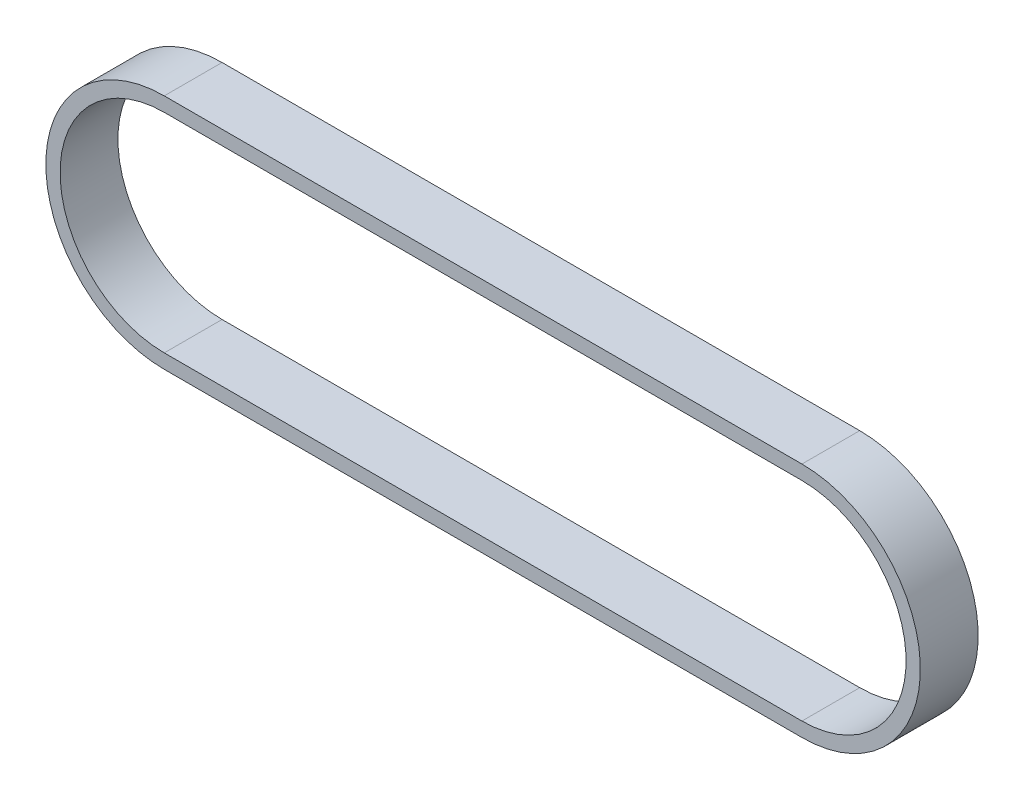
SolidWorks part; units mm, degrees
ref_plane "Plano frontal" through (0, 0, 0) normal (0, 0, 1) x (1, 0, 0)
ref_plane "Plano superior" through (0, 0, 0) normal (0, 1, 0) x (1, 0, 0)
ref_plane "Plano direito" through (0, 0, 0) normal (1, 0, 0) x (0, 0, -1)
sketch "Esboço1" plane through (0, 0, 0) normal (0, 0, 1) x (1, 0, 0)
  line L0 (0, 0) -> (105, 0) construction
  line L1 (0, 19.5) -> (105, 19.5)
  line L2 (0, -19.5) -> (105, -19.5)
  line L3 (0, 17.15) -> (105, 17.15)
  line L4 (0, -17.15) -> (105, -17.15)
  arc A0 (0, 19.5) -> (0, -19.5) centre (0, 0) ccw
  arc A1 (105, -19.5) -> (105, 19.5) centre (105, 0) ccw
  arc A2 (105, -17.15) -> (105, 17.15) centre (105, 0) ccw
  arc A3 (0, 17.15) -> (0, -17.15) centre (0, 0) ccw
  point P3 (52.5, 0)
  dimension "D1" = 19.5
  dimension "D2" = 105
  dimension "D3" = 2.35
extrude "Ressalto-extrusão1" add sketch "Esboço1" along normal blind 9.52
